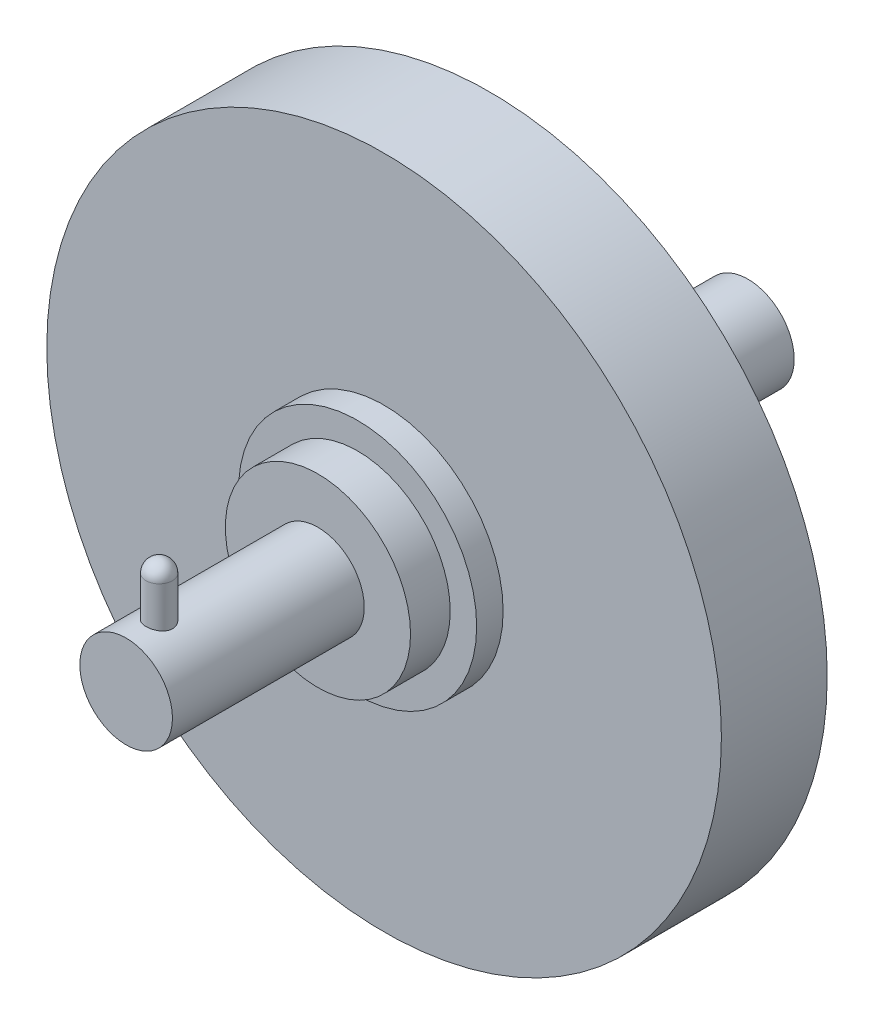
SolidWorks part; units mm, degrees
ref_plane "Front Plane" through (0, 0, 0) normal (0, 0, 1) x (1, 0, 0)
ref_plane "Top Plane" through (0, 0, 0) normal (0, 1, 0) x (1, 0, 0)
ref_plane "Right Plane" through (0, 0, 0) normal (1, 0, 0) x (0, 0, -1)
sketch "Sketch1" plane through (0, 0, 0) normal (0, 0, 1) x (1, 0, 0)
  circle A1 centre (0, 0) radius 323.85
  dimension "D1" = 647.7
extrude "Boss-Extrude3" add sketch "Sketch1" along normal blind 101.6 contours A1
sketch "Sketch2" plane through (0, 0, 101.6) normal (0, 0, 1) x (1, 0, 0)
  circle A0 centre (0, 0) radius 114.3
  dimension "D1" = 228.6
extrude "Boss-Extrude4" add sketch "Sketch2" along normal blind 25.4 and the other way blind 127 contours A0
sketch "Sketch4" plane through (0, 0, 127) normal (0, 0, 1) x (1, 0, 0)
  circle A0 centre (0, 0) radius 88.9
  dimension "D1" = 177.8
extrude "Boss-Extrude5" add sketch "Sketch4" along normal blind 38.1 and the other way blind 190.5
sketch "Sketch5" plane through (0, 0, 165.1) normal (0, 0, 1) x (1, 0, 0)
  circle A0 centre (0, 0) radius 44.45
  dimension "D1" = 88.9
extrude "Boss-Extrude6" add sketch "Sketch5" along normal blind 184.15 and the other way blind 412.75
ref_plane "Plane1" through (0, 44.45, 0) normal (0, 1, 0) x (1, 0, 0)
sketch "Sketch6" plane through (0, 44.45, 0) normal (0, 1, 0) x (1, 0, 0)
  line L0 (0, -349.25) -> (0, -317.5) construction
  line L1 (-44.45, -349.25) -> (44.45, -349.25) construction
  line L2 (-44.45, -317.5) -> (44.45, -317.5) construction
  line L3 (-44.45, -165.1) -> (-44.45, -349.25) construction
  line L4 (44.45, -349.25) -> (44.45, -165.1) construction
  circle A0 centre (0, -317.5) radius 12.7
  point P12 (0, -317.5)
  dimension "D2" = 25.4
  dimension "D1" = 31.75
extrude "Boss-Extrude7" add sketch "Sketch6" along normal blind 50.8 and the other way blind 25.4
fillet "Fillet2" radius 12.7 1 edges at (0, 95.25, 330.2)
